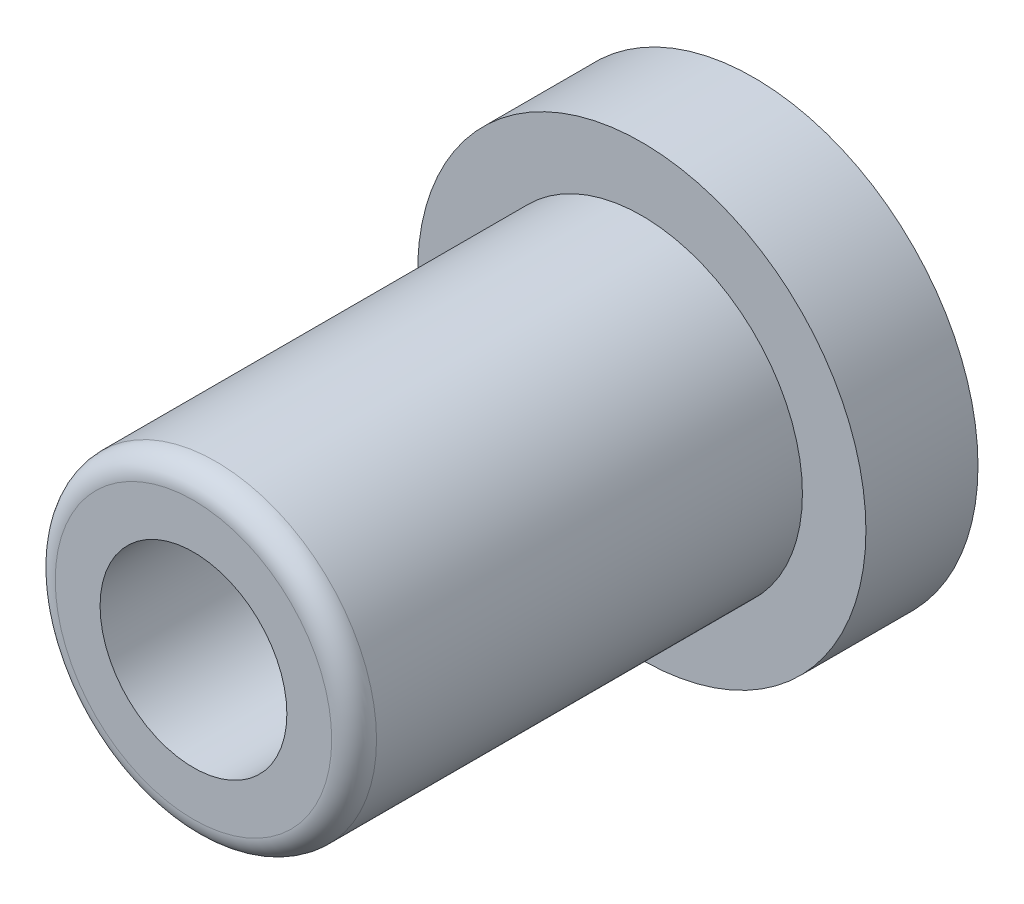
SolidWorks part; units mm, degrees
ref_plane "Plano frontal" through (0, 0, 0) normal (0, 0, 1) x (1, 0, 0)
ref_plane "Plano superior" through (0, 0, 0) normal (0, 1, 0) x (1, 0, 0)
ref_plane "Plano direito" through (0, 0, 0) normal (1, 0, 0) x (0, 0, -1)
sketch "Esboço1" plane through (0, 0, 0) normal (0, 0, 1) x (1, 0, 0)
  circle A0 centre (-15.3413, 7.9152) radius 3
  dimension "D1" = 6
extrude "Ressalto-extrusão1" add sketch "Esboço1" along normal blind 1.5
sketch "Esboço2" plane through (0, 0, 1.5) normal (0, 0, 1) x (1, 0, 0)
  circle A0 centre (-15.3413, 7.9152) radius 2.15
  dimension "D1" = 4.3
extrude "Ressalto-extrusão2" add sketch "Esboço2" along normal blind 6
hole_wizard "Broca de rosquear para tarraxa de M3x0.51" positions "Esboço4" profile "Esboço3" hole size "M3x0.5" standard "Métrico Ansi" end condition up to next
sketch "Esboço4" plane through (0, 0, 0) normal (0, 0, -1) x (-1, 0, 0)
  point P0 (15.3413, 7.9152)
sketch "Esboço3" plane through (-15.3413, 7.9152, 0) normal (1, 0, 0) x (0, 1, 0)
  line L0 (0, 0) -> (0, 7.5)
  line L1 (0, 7.5) -> (1.25, 7.5)
  line L2 (1.25, 7.5) -> (1.25, 0)
  line L5 (1.25, 0) -> (0, 0)
  line L11 (0, -6.35) -> (0, 107.95) construction
  dimension "Thru Hole Dia." = 2.5
  dimension "Thru Hole Depth" = 7.5
cosmetic thread "Representação de rosca1" parameters "D2"=3
fillet "Filete1" radius 0.3 1 edges at (-13.1913, 7.9152, 7.5)
